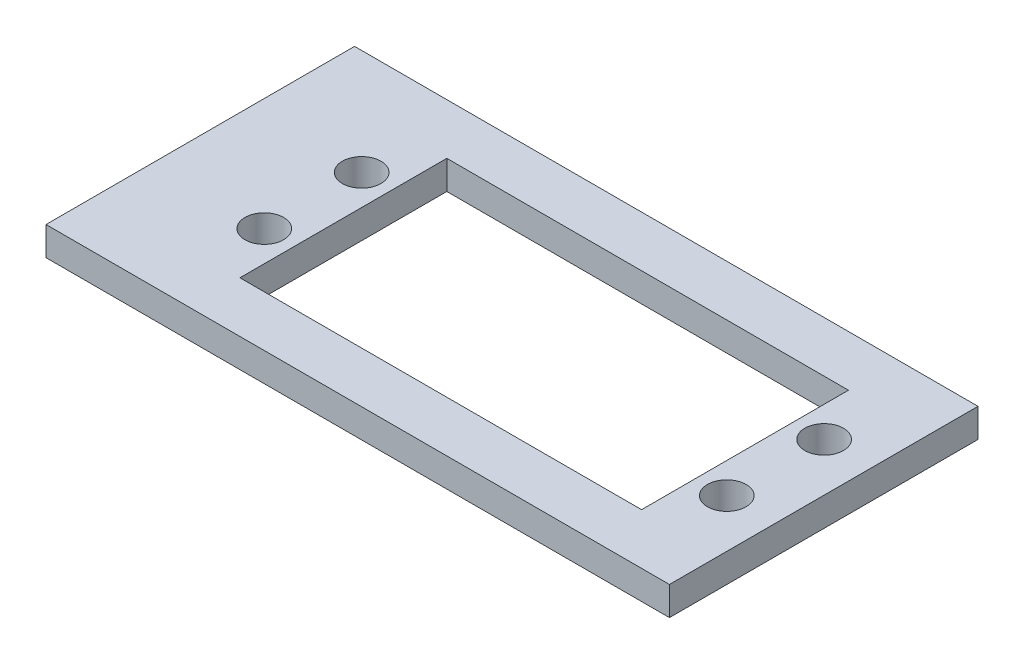
SolidWorks part; units mm, degrees
ref_plane "Front Plane" through (0, 0, 0) normal (0, 0, 1) x (1, 0, 0)
ref_plane "Top Plane" through (0, 0, 0) normal (0, 1, 0) x (1, 0, 0)
ref_plane "Right Plane" through (0, 0, 0) normal (1, 0, 0) x (0, 0, -1)
sketch "Sketch1" plane through (0, 0, 0) normal (0, 1, 0) x (1, 0, 0)
  line L0 (0.1896, 20.8674) -> (0.1896, 26.1714)
  line L1 (-41.7204, 12.01) -> (-41.7204, 8.0823)
  line L2 (-41.7204, 20.8674) -> (-41.7204, 26.1714)
  line L3 (-41.7204, -0.7226) -> (0.1896, -0.7226)
  line L4 (-41.7204, -0.7226) -> (-41.7204, 8.0823)
  line L5 (-41.7204, 20.8674) -> (0.1896, 20.8674)
  line L6 (0.1896, -0.7226) -> (0.1896, 20.8674)
  line L7 (-41.7204, -0.7226) -> (0.1896, 20.8674) construction
  line L8 (-41.7204, 20.8674) -> (0.1896, -0.7226) construction
  line L9 (-44.8954, 4.9924) -> (3.3646, 4.9924) construction
  line L10 (-44.8954, 4.9924) -> (-44.8954, 7.0117) construction
  line L11 (-44.8954, 15.1524) -> (3.3646, 15.1524) construction
  line L12 (3.3646, 4.9924) -> (3.3646, 15.1524) construction
  line L13 (-44.8954, 4.9924) -> (3.3646, 15.1524) construction
  line L14 (-44.8954, 15.1524) -> (3.3646, 4.9924) construction
  line L15 (-41.7204, 12.01) -> (-41.7204, 20.8674)
  line L16 (-41.7204, 10.0724) -> (13.9846, 10.0724) construction
  line L17 (15.1226, -6.0267) -> (-56.6535, -6.0267)
  line L18 (15.1226, -6.0267) -> (15.1226, 26.1714)
  line L19 (15.1226, 26.1714) -> (-56.6535, 26.1714)
  line L20 (-56.6535, -6.0267) -> (-56.6535, 26.1714)
  line L21 (-44.8954, 13.1331) -> (-44.8954, 15.1524) construction
  line L22 (8.4021, 26.1714) -> (8.4021, -6.0267)
  circle A0 centre (3.3646, 15.1524) radius 2.0193
  circle A1 centre (3.3646, 4.9924) radius 2.0193
  circle A2 centre (-44.8954, 15.1524) radius 2.0193
  circle A3 centre (-44.8954, 4.9924) radius 2.0193
  point P6 (-20.7654, 10.0724)
  point P11 (-20.7654, 10.0724)
  point P23 (-20.7654, 26.1714)
  dimension "D1" = 4.0386
  dimension "D2" = 14.9331
extrude "Boss-Extrude1" add sketch "Sketch1" along normal blind 3 contours L22 L19 L0 L6 L3 L4 L1 L15 L2 L20 L17 A3 A2 A1 A0 | L0 L19 L2 L5
